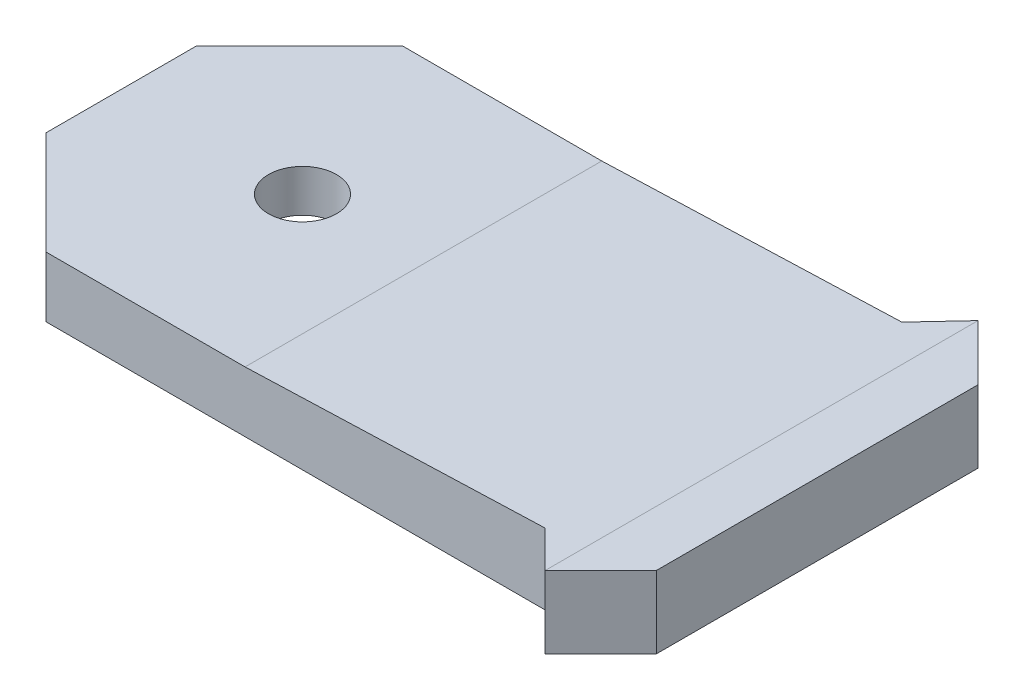
SolidWorks part; units mm, degrees
ref_plane "Front Plane" through (0, 0, 0) normal (0, 0, 1) x (1, 0, 0)
ref_plane "Top Plane" through (0, 0, 0) normal (0, 1, 0) x (1, 0, 0)
ref_plane "Right Plane" through (0, 0, 0) normal (1, 0, 0) x (0, 0, -1)
sketch "Sketch1" plane through (0, 0, 0) normal (0, 1, 0) x (1, 0, 0)
  line L0 (0, 4.9706) -> (0, -4.9706)
  line L1 (0, -4.9706) -> (7.0294, -12) construction
  line L2 (7.0294, -12) -> (40.0529, -12) construction
  line L3 (40.0529, -12) -> (42.3719, -14.3189)
  line L4 (42.3719, -14.3189) -> (46.0488, -10.642)
  line L5 (46.0488, -10.642) -> (46.0488, 10.642)
  line L6 (46.0488, 10.642) -> (42.3719, 14.3189)
  line L7 (42.3719, 14.3189) -> (40.0529, 12)
  line L8 (40.0529, 12) -> (7.0294, 12) construction
  line L9 (7.0294, 12) -> (0, 4.9706) construction
  line L10 (0, 0) -> (12, 0) construction
  line L11 (0, 4.9706) -> (6.8394, 11.81) construction
  line L12 (6.8394, 11.81) -> (39.8629, 11.81) construction
  line L13 (39.8629, 11.81) -> (40.0529, 12)
  line L14 (0, -4.9706) -> (6.8394, -11.81) construction
  line L15 (6.8394, -11.81) -> (39.8629, -11.81) construction
  line L16 (39.8629, -11.81) -> (40.0529, -12)
  line L17 (0, 4.9706) -> (6.8294, 11.8)
  line L18 (6.8294, 11.8) -> (39.8529, 11.8)
  line L19 (39.8529, 11.8) -> (39.8629, 11.81)
  line L20 (0, -4.9706) -> (6.8294, -11.8)
  line L21 (6.8294, -11.8) -> (39.8529, -11.8)
  line L22 (39.8529, -11.8) -> (39.8629, -11.81)
  line L23 (12, 0) -> (12, 12) construction
  line L24 (24, 4.4323) -> (38.1292, 18.5616) construction
  line L25 (24, 4.4323) -> (24, 0) construction
  line L26 (38.1292, 18.5616) -> (42.3719, 14.3189) construction
  line L27 (12, 0) -> (24, 0) construction
  line L28 (24, -4.4323) -> (24, 0) construction
  line L29 (24, -4.4323) -> (38.1292, -18.5616) construction
  line L30 (38.1292, -18.5616) -> (42.3719, -14.3189) construction
  circle A0 centre (12, 0) radius 2.25
  circle A1 centre (12, 0) radius 10 construction
  point P10 (0, 0)
  point P26 (31.5677, -12)
  dimension "D6" = 4.5
  dimension "D5" = 20
  dimension "D1" = 45
  dimension "D2" = 45
  dimension "D3" = 135
  dimension "D4" = 135
  dimension "D7" = 12
  dimension "D8" = 9.2794
  dimension "D9" = 5.2
  dimension "D10" = 0.2
  dimension "D11" = 40.0529
  dimension "D12" = 0.01
  dimension "D13" = 6
extrude "Boss-Extrude1" add sketch "Sketch1" along normal blind 6
sketch "Sketch2" plane through (0, 0, 0) normal (0, -1, 0) x (1, 0, 0)
  circle A0 centre (12, 0) radius 10 construction
  circle A1 centre (12, 0) radius 10
extrude "Cut-Extrude1" cut sketch "Sketch2" against normal blind 1.2
sketch "Sketch3" plane through (0, 0, -11.8) normal (0, 0, -1) x (-1, 0, 0)
  line L1 (-46.0488, 6) -> (0, 6)
  line L3 (-46.0488, 6) -> (-46.0488, 0) construction
  line L4 (0, 6) -> (0, 0) construction
  line L6 (-20, 4) -> (0, 4)
  line L7 (0, 4) -> (0, 6)
  line L9 (-46.0488, 4.7812) -> (-46.0488, 6)
  line L10 (-6.8294, 0) -> (0, 0) construction
  line L11 (-42.3719, 6) -> (-39.8529, 6) construction
  line L12 (-20, 4) -> (-42.3719, 4.7812)
  line L13 (-42.3719, 4.7812) -> (-46.0488, 4.7812)
  line L14 (-42.3719, 6) -> (-42.3719, 0) construction
  dimension "D1" = 20
  dimension "D2" = 4
  dimension "D3" = 178
extrude "Cut-Extrude2" cut sketch "Sketch3" against normal through all both and the other way through all
